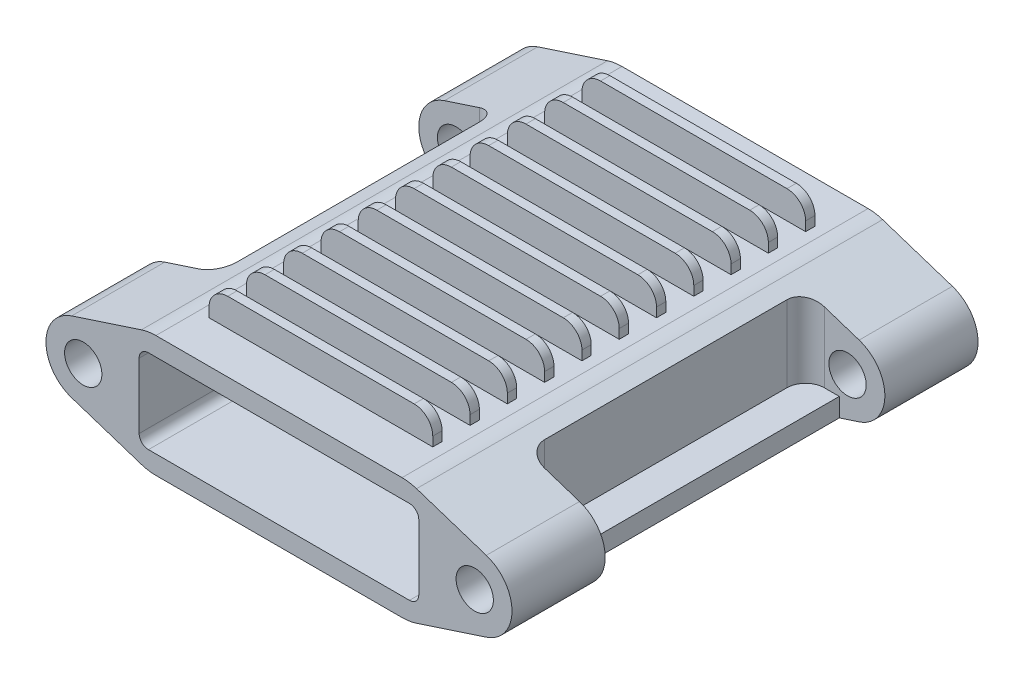
SolidWorks part; units mm, degrees
ref_plane "Front Plane" through (0, 0, 0) normal (0, 0, 1) x (1, 0, 0)
ref_plane "Top Plane" through (0, 0, 0) normal (0, 1, 0) x (1, 0, 0)
ref_plane "Right Plane" through (0, 0, 0) normal (1, 0, 0) x (0, 0, -1)
sketch "Sketch1" plane through (0, 0, 0) normal (0, 0, 1) x (1, 0, 0)
  line L0 (-25, 0) -> (25, 0) construction
  line L1 (-13.2025, 6.5) -> (13.2025, 6.5)
  line L3 (-13.2025, -6.5) -> (13.2025, -6.5)
  line L5 (0, 6.5) -> (0, -6.5) construction
  line L6 (-22.2443, 3.8015) -> (-14.7579, 6.2519)
  line L7 (-14, 4.5) -> (14, 4.5)
  line L8 (-15, 3.5) -> (-15, -3.5)
  line L9 (-14, -4.5) -> (14, -4.5)
  line L10 (15, 3.5) -> (15, -3.5)
  line L11 (-22.2443, -3.8015) -> (-14.7579, -6.2519)
  line L12 (22.2443, 3.8015) -> (14.7579, 6.2519)
  line L13 (22.2443, -3.8015) -> (14.7579, -6.2519)
  circle A0 centre (-21, 0) radius 2
  circle A1 centre (21, 0) radius 2
  arc A2 (-22.2443, 3.8015) -> (-22.2443, -3.8015) centre (-21, 0) ccw
  arc A3 (22.2443, -3.8015) -> (22.2443, 3.8015) centre (21, 0) ccw
  arc A4 (14.7579, 6.2519) -> (13.2025, 6.5) centre (13.2025, 1.5) ccw
  arc A5 (14.7579, -6.2519) -> (13.2025, -6.5) centre (13.2025, -1.5) cw
  arc A6 (-14.7579, -6.2519) -> (-13.2025, -6.5) centre (-13.2025, -1.5) ccw
  arc A7 (-14.7579, 6.2519) -> (-13.2025, 6.5) centre (-13.2025, 1.5) cw
  arc A8 (14, 4.5) -> (15, 3.5) centre (14, 3.5) cw
  arc A9 (14, -4.5) -> (15, -3.5) centre (14, -3.5) ccw
  arc A10 (-15, -3.5) -> (-14, -4.5) centre (-14, -3.5) ccw
  arc A11 (-14, 4.5) -> (-15, 3.5) centre (-14, 3.5) ccw
  point P2 (14, 6.5)
  point P24 (14, -6.5)
  point P29 (-14, -6.5)
  point P32 (-14, 6.5)
  dimension "D1" = 4
  dimension "D9" = 4
  dimension "D10" = 4
  dimension "D11" = 4
  dimension "D17" = 5
  dimension "D18" = 1
  dimension "D2" = 13
  dimension "D3" = 21
  dimension "D4" = 21
  dimension "D5" = 30
  dimension "D6" = 9
  dimension "D7" = 15
  dimension "D8" = 4.5
  dimension "D12" = 6.5
  dimension "D13" = 14
  dimension "D14" = 14
  dimension "D15" = 14
  dimension "D16" = 14
extrude "Boss-Extrude1" add sketch "Sketch1" along normal blind 10
sketch "Sketch2" plane through (0, 0, 10) normal (0, 0, 1) x (1, 0, 0)
  line L0 (13.2025, 6.5) -> (-13.2025, 6.5) construction
  line L1 (-14, 4.5) -> (14, 4.5)
  line L2 (-15, 3.5) -> (-15, -3.5)
  line L3 (-14, -4.5) -> (14, -4.5)
  line L4 (15, 3.5) -> (15, -3.5)
  line L5 (-13.2025, -6.5) -> (13.2025, -6.5) construction
  line L6 (-16.5, 5.6817) -> (-14.7579, 6.2519)
  line L7 (-13.2025, 6.5) -> (13.2025, 6.5)
  line L8 (-16.5, 5.6817) -> (-16.5, -2.5)
  line L9 (-13.2025, -6.5) -> (13.2025, -6.5)
  line L10 (16.5, 5.6817) -> (16.5, -2.5)
  line L11 (-14.7579, 6.2519) -> (-22.2443, 3.8015) construction
  line L12 (-16.5, -5.6817) -> (-14.7579, -6.2519)
  line L13 (-22.2443, -3.8015) -> (-14.7579, -6.2519) construction
  line L14 (16.5, 5.6817) -> (14.7579, 6.2519)
  line L15 (22.2443, 3.8015) -> (14.7579, 6.2519) construction
  line L16 (16.5, -5.6817) -> (14.7579, -6.2519)
  line L17 (14.7579, -6.2519) -> (22.2443, -3.8015) construction
  line L18 (-16.5, -4.5) -> (-20.1104, -4.5)
  line L19 (-20.1104, -4.5) -> (-20.1104, -2.5)
  line L20 (-20.1104, -2.5) -> (-16.5, -2.5)
  line L21 (-16.5, -4.5) -> (-16.5, -5.6817)
  line L22 (16.5, -4.5) -> (20.1104, -4.5)
  line L23 (20.1104, -4.5) -> (20.1104, -2.5)
  line L24 (20.1104, -2.5) -> (16.5, -2.5)
  line L25 (16.5, -4.5) -> (16.5, -5.6817)
  arc A0 (22.2443, -3.8015) -> (22.2443, 3.8015) centre (21, 0) ccw construction
  circle A1 centre (-21, 0) radius 2 construction
  arc A2 (-15, -3.5) -> (-14, -4.5) centre (-14, -3.5) ccw
  arc A3 (14, -4.5) -> (15, -3.5) centre (14, -3.5) ccw
  arc A4 (14, 4.5) -> (15, 3.5) centre (14, 3.5) cw
  arc A5 (-14, 4.5) -> (-15, 3.5) centre (-14, 3.5) ccw
  arc A6 (14.7579, -6.2519) -> (13.2025, -6.5) centre (13.2025, -1.5) cw
  arc A7 (14.7579, 6.2519) -> (13.2025, 6.5) centre (13.2025, 1.5) ccw
  arc A8 (-14.7579, 6.2519) -> (-13.2025, 6.5) centre (-13.2025, 1.5) cw
  arc A9 (-14.7579, -6.2519) -> (-13.2025, -6.5) centre (-13.2025, -1.5) ccw
  dimension "D5" = 1
  dimension "D1" = 2
  dimension "D2" = 2
  dimension "D3" = 6
  dimension "D4" = 6
  dimension "D6" = 33
  dimension "D7" = 2
  dimension "D8" = 2
  dimension "D9" = 31.5
  dimension "D10" = 2
  dimension "D11" = 2
extrude "Boss-Extrude2" add sketch "Sketch2" along normal blind 30
sketch "Sketch3" plane through (0, 0, 40) normal (0, 0, 1) x (1, 0, 0)
  line L0 (-25, 0) -> (25, 0) construction
  line L1 (-13.2025, 6.5) -> (13.2025, 6.5)
  line L2 (-13.2025, -6.5) -> (13.2025, -6.5)
  line L3 (0, 6.5) -> (0, -6.5) construction
  line L4 (-22.2443, 3.8015) -> (-14.7579, 6.2519)
  line L5 (-14, 4.5) -> (14, 4.5)
  line L6 (-15, 3.5) -> (-15, -3.5)
  line L7 (-14, -4.5) -> (14, -4.5)
  line L8 (15, 3.5) -> (15, -3.5)
  line L9 (-22.2443, -3.8015) -> (-14.7579, -6.2519)
  line L10 (22.2443, 3.8015) -> (14.7579, 6.2519)
  line L11 (22.2443, -3.8015) -> (14.7579, -6.2519)
  circle A0 centre (-21, 0) radius 2
  circle A1 centre (21, 0) radius 2
  arc A2 (-22.2443, 3.8015) -> (-22.2443, -3.8015) centre (-21, 0) ccw
  arc A3 (22.2443, -3.8015) -> (22.2443, 3.8015) centre (21, 0) ccw
  arc A4 (14.7579, 6.2519) -> (13.2025, 6.5) centre (13.2025, 1.5) ccw
  arc A5 (14.7579, -6.2519) -> (13.2025, -6.5) centre (13.2025, -1.5) cw
  arc A6 (-14.7579, -6.2519) -> (-13.2025, -6.5) centre (-13.2025, -1.5) ccw
  arc A7 (-14.7579, 6.2519) -> (-13.2025, 6.5) centre (-13.2025, 1.5) cw
  arc A8 (14, 4.5) -> (15, 3.5) centre (14, 3.5) cw
  arc A9 (14, -4.5) -> (15, -3.5) centre (14, -3.5) ccw
  arc A10 (-15, -3.5) -> (-14, -4.5) centre (-14, -3.5) ccw
  arc A11 (-14, 4.5) -> (-15, 3.5) centre (-14, 3.5) ccw
  point P0 (3.5269, 4.5)
extrude "Boss-Extrude3" add sketch "Sketch3" along normal blind 10
sketch "Sketch4" plane through (0, 6.5, 0) normal (0, 1, 0) x (1, 0, 0)
  line L0 (13.2025, 0) -> (-13.2025, 0) construction
  line L1 (-12, -4.5) -> (12, -4.5)
  line L2 (-12, -4.5) -> (-12, -5.5)
  line L3 (-12, -5.5) -> (12, -5.5)
  line L4 (12, -4.5) -> (12, -5.5)
  line L6 (-12, -8.5) -> (12, -8.5)
  line L7 (-12, -9.5) -> (12, -9.5)
  line L8 (12, -8.5) -> (12, -9.5)
  line L9 (-12, -8.5) -> (-12, -9.5)
  line L10 (-12, -12.5) -> (12, -12.5)
  line L11 (-12, -13.5) -> (12, -13.5)
  line L12 (12, -12.5) -> (12, -13.5)
  line L13 (-12, -12.5) -> (-12, -13.5)
  line L14 (-12, -16.5) -> (12, -16.5)
  line L15 (-12, -17.5) -> (12, -17.5)
  line L16 (12, -16.5) -> (12, -17.5)
  line L17 (-12, -16.5) -> (-12, -17.5)
  line L18 (-12, -20.5) -> (12, -20.5)
  line L19 (-12, -21.5) -> (12, -21.5)
  line L20 (12, -20.5) -> (12, -21.5)
  line L21 (-12, -20.5) -> (-12, -21.5)
  line L22 (-12, -24.5) -> (12, -24.5)
  line L23 (-12, -25.5) -> (12, -25.5)
  line L24 (12, -24.5) -> (12, -25.5)
  line L25 (-12, -24.5) -> (-12, -25.5)
  line L26 (-12, -28.5) -> (12, -28.5)
  line L27 (-12, -29.5) -> (12, -29.5)
  line L28 (12, -28.5) -> (12, -29.5)
  line L29 (-12, -28.5) -> (-12, -29.5)
  line L30 (-12, -32.5) -> (12, -32.5)
  line L31 (-12, -33.5) -> (12, -33.5)
  line L32 (12, -32.5) -> (12, -33.5)
  line L33 (-12, -32.5) -> (-12, -33.5)
  line L34 (-12, -36.5) -> (12, -36.5)
  line L35 (-12, -37.5) -> (12, -37.5)
  line L36 (12, -36.5) -> (12, -37.5)
  line L37 (-12, -36.5) -> (-12, -37.5)
  line L38 (-12, -40.5) -> (12, -40.5)
  line L39 (-12, -41.5) -> (12, -41.5)
  line L40 (12, -40.5) -> (12, -41.5)
  line L41 (-12, -40.5) -> (-12, -41.5)
  line L42 (-12, -44.5) -> (12, -44.5)
  line L43 (-12, -45.5) -> (12, -45.5)
  line L44 (12, -44.5) -> (12, -45.5)
  line L45 (-12, -44.5) -> (-12, -45.5)
  line L62 (-12, -4.5) -> (-12, -8.5) construction
  point P6 (0, 0)
  point P8 (0, 0)
  dimension "D1" = 1
  dimension "D2" = 4.5
  dimension "D3" = 12
  dimension "D4" = 12
  dimension "D5" = 11
  dimension "D6" = 4
extrude "Boss-Extrude4" add sketch "Sketch4" along normal blind 3
fillet "Fillet1" radius 2 22 edges at (12, 9.5, 5) (12, 9.5, 9) (12, 9.5, 13) (12, 9.5, 17) (12, 9.5, 21) (12, 9.5, 25) (12, 9.5, 29) (12, 9.5, 33) (12, 9.5, 37) (12, 9.5, 41) (12, 9.5, 45) (-12, 9.5, 45) (-12, 9.5, 41) (-12, 9.5, 37) (-12, 9.5, 33) (-12, 9.5, 29) (-12, 9.5, 25) (-12, 9.5, 21) (-12, 9.5, 17) (-12, 9.5, 13) (-12, 9.5, 9) (-12, 9.5, 5)
sketch "Sketch5" plane through (0, -6.5, 0) normal (0, -1, 0) x (-1, 0, 0)
  line L1 (-12, -4.5) -> (12, -4.5)
  line L2 (-12, -4.5) -> (-12, -5.5)
  line L3 (-12, -5.5) -> (12, -5.5)
  line L4 (12, -4.5) -> (12, -5.5)
  line L6 (-12, -8.5) -> (12, -8.5)
  line L7 (-12, -9.5) -> (12, -9.5)
  line L8 (12, -8.5) -> (12, -9.5)
  line L9 (-12, -8.5) -> (-12, -9.5)
  line L10 (-12, -12.5) -> (12, -12.5)
  line L11 (-12, -13.5) -> (12, -13.5)
  line L12 (12, -12.5) -> (12, -13.5)
  line L13 (-12, -12.5) -> (-12, -13.5)
  line L14 (-12, -16.5) -> (12, -16.5)
  line L15 (-12, -17.5) -> (12, -17.5)
  line L16 (12, -16.5) -> (12, -17.5)
  line L17 (-12, -16.5) -> (-12, -17.5)
  line L18 (-12, -20.5) -> (12, -20.5)
  line L19 (-12, -21.5) -> (12, -21.5)
  line L20 (12, -20.5) -> (12, -21.5)
  line L21 (-12, -20.5) -> (-12, -21.5)
  line L22 (-12, -24.5) -> (12, -24.5)
  line L23 (-12, -25.5) -> (12, -25.5)
  line L24 (12, -24.5) -> (12, -25.5)
  line L25 (-12, -24.5) -> (-12, -25.5)
  line L26 (-12, -28.5) -> (12, -28.5)
  line L27 (-12, -29.5) -> (12, -29.5)
  line L28 (12, -28.5) -> (12, -29.5)
  line L29 (-12, -28.5) -> (-12, -29.5)
  line L30 (-12, -32.5) -> (12, -32.5)
  line L31 (-12, -33.5) -> (12, -33.5)
  line L32 (12, -32.5) -> (12, -33.5)
  line L33 (-12, -32.5) -> (-12, -33.5)
  line L34 (-12, -36.5) -> (12, -36.5)
  line L35 (-12, -37.5) -> (12, -37.5)
  line L36 (12, -36.5) -> (12, -37.5)
  line L37 (-12, -36.5) -> (-12, -37.5)
  line L38 (-12, -40.5) -> (12, -40.5)
  line L39 (-12, -41.5) -> (12, -41.5)
  line L40 (12, -40.5) -> (12, -41.5)
  line L41 (-12, -40.5) -> (-12, -41.5)
  line L42 (-12, -44.5) -> (12, -44.5)
  line L43 (-12, -45.5) -> (12, -45.5)
  line L44 (12, -44.5) -> (12, -45.5)
  line L45 (-12, -44.5) -> (-12, -45.5)
  line L62 (-12, -4.5) -> (-12, -8.5) construction
  line L63 (14.7579, 0) -> (13.2025, 0) construction
  line L64 (13.2025, 0) -> (-13.2025, 0) construction
  point P7 (0, 0)
  dimension "D1" = 1
  dimension "D2" = 4.5
  dimension "D3" = 12
  dimension "D4" = 12
  dimension "D5" = 11
  dimension "D6" = 4
extrude "Boss-Extrude5" add sketch "Sketch5" along normal blind 3
fillet "Fillet2" radius 2 22 edges at (-12, -9.5, 5) (-12, -9.5, 9) (-12, -9.5, 13) (-12, -9.5, 17) (-12, -9.5, 21) (-12, -9.5, 25) (-12, -9.5, 29) (-12, -9.5, 33) (-12, -9.5, 37) (-12, -9.5, 41) (-12, -9.5, 45) (12, -9.5, 45) (12, -9.5, 41) (12, -9.5, 37) (12, -9.5, 33) (12, -9.5, 29) (12, -9.5, 25) (12, -9.5, 21) (12, -9.5, 17) (12, -9.5, 13) (12, -9.5, 9) (12, -9.5, 5)
fillet "Fillet3" radius 2 8 edges
